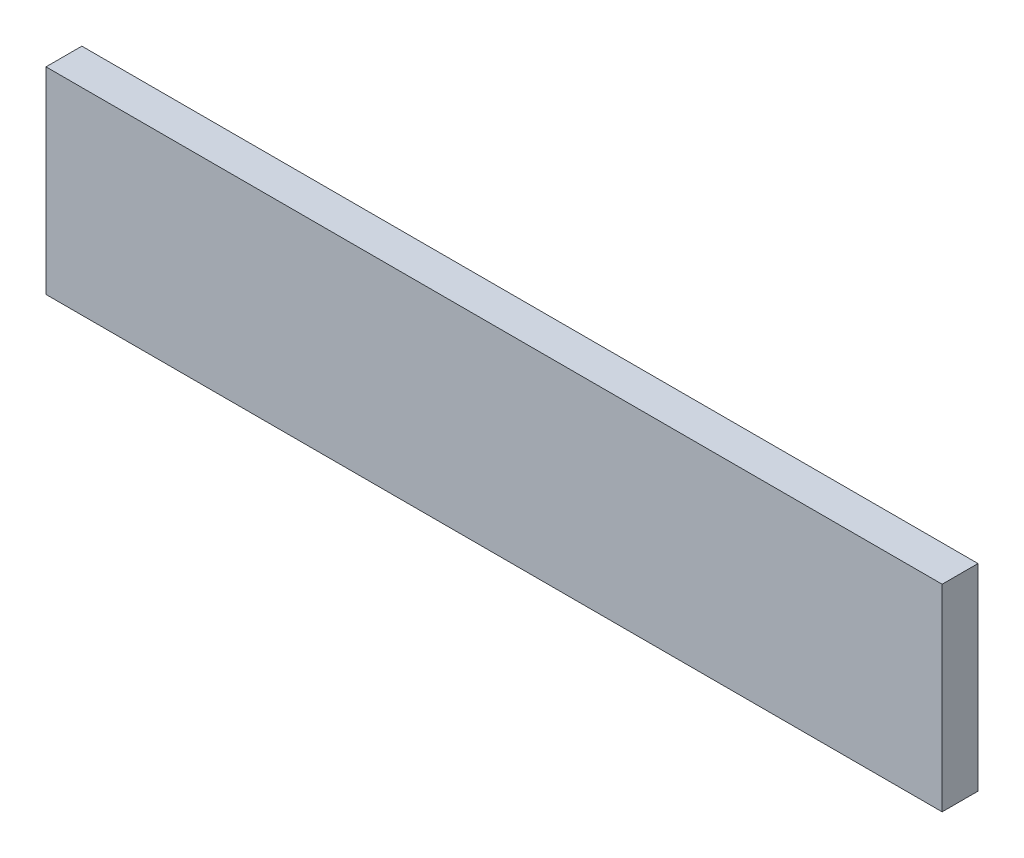
SolidWorks part; units mm, degrees
ref_plane "Front Plane" through (0, 0, 0) normal (0, 0, 1) x (1, 0, 0)
ref_plane "Top Plane" through (0, 0, 0) normal (0, 1, 0) x (1, 0, 0)
ref_plane "Right Plane" through (0, 0, 0) normal (1, 0, 0) x (0, 0, -1)
sketch "Sketch1" plane through (0, 0, 0) normal (0, 0, 1) x (1, 0, 0)
  line L1 (-125, 27.5) -> (125, 27.5)
  line L2 (-125, 27.5) -> (-125, -27.5)
  line L3 (-125, -27.5) -> (125, -27.5)
  line L4 (125, 27.5) -> (125, -27.5)
  line L5 (-125, 27.5) -> (125, -27.5) construction
  line L6 (-125, -27.5) -> (125, 27.5) construction
  point P0 (0, 0)
  dimension "D1" = 250
  dimension "D2" = 55
extrude "Boss-Extrude1" add sketch "Sketch1" along normal blind 10
